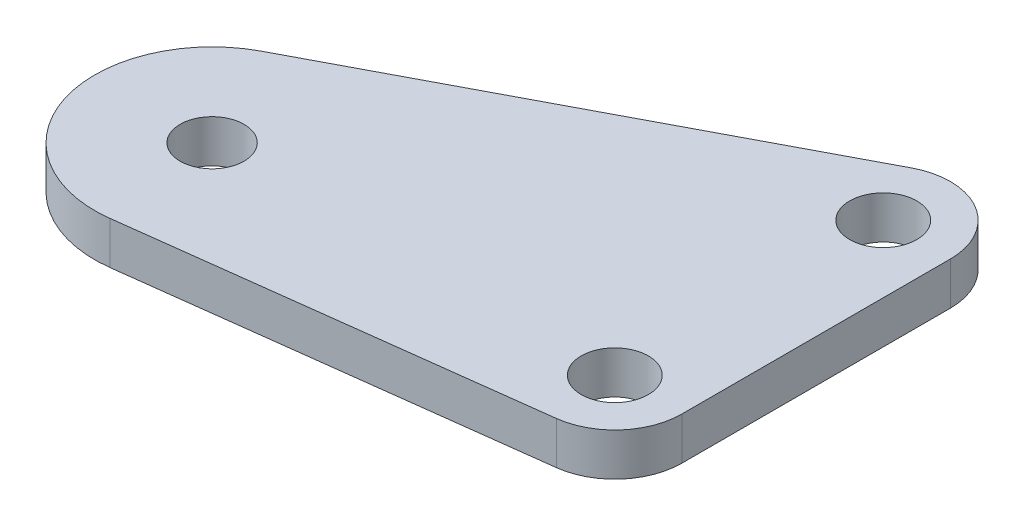
SolidWorks part; units mm, degrees
material "6061 Alloy"
ref_plane "Front Plane" through (0, 0, 0) normal (0, 0, 1) x (1, 0, 0)
ref_plane "Top Plane" through (0, 0, 0) normal (0, 1, 0) x (1, 0, 0)
ref_plane "Right Plane" through (0, 0, 0) normal (1, 0, 0) x (0, 0, -1)
sketch "Sketch1" plane through (0, 0, 0) normal (0, 1, 0) x (1, 0, 0)
  line L0 (0, 0) -> (0, 40) construction
  line L1 (0, 0) -> (-60, 0) construction
  line L2 (10, 40) -> (10, 0)
  line L3 (-57.8125, -17.3627) -> (1.25, -9.9216)
  line L4 (-68.1402, 15.4915) -> (-4.6515, 48.8523)
  circle A0 centre (0, 0) radius 5
  circle A1 centre (0, 40) radius 5
  circle A2 centre (-60, 0) radius 4.7625
  arc A3 (-4.6515, 48.8523) -> (10, 40) centre (0, 40) cw
  arc A4 (-68.1402, 15.4915) -> (-57.8125, -17.3627) centre (-60, 0) ccw
  arc A5 (10, 0) -> (1.25, -9.9216) centre (0, 0) cw
  dimension "D2" = 10
  dimension "D3" = 9.525
  dimension "D4" = 10
  dimension "D6" = 10
  dimension "D7" = 17.5
  dimension "D1" = 60
  dimension "D5" = 40
extrude "Boss-Extrude1" add sketch "Sketch1" against normal blind 6.35 contours L4 A3 L2 A5 L3 A4
